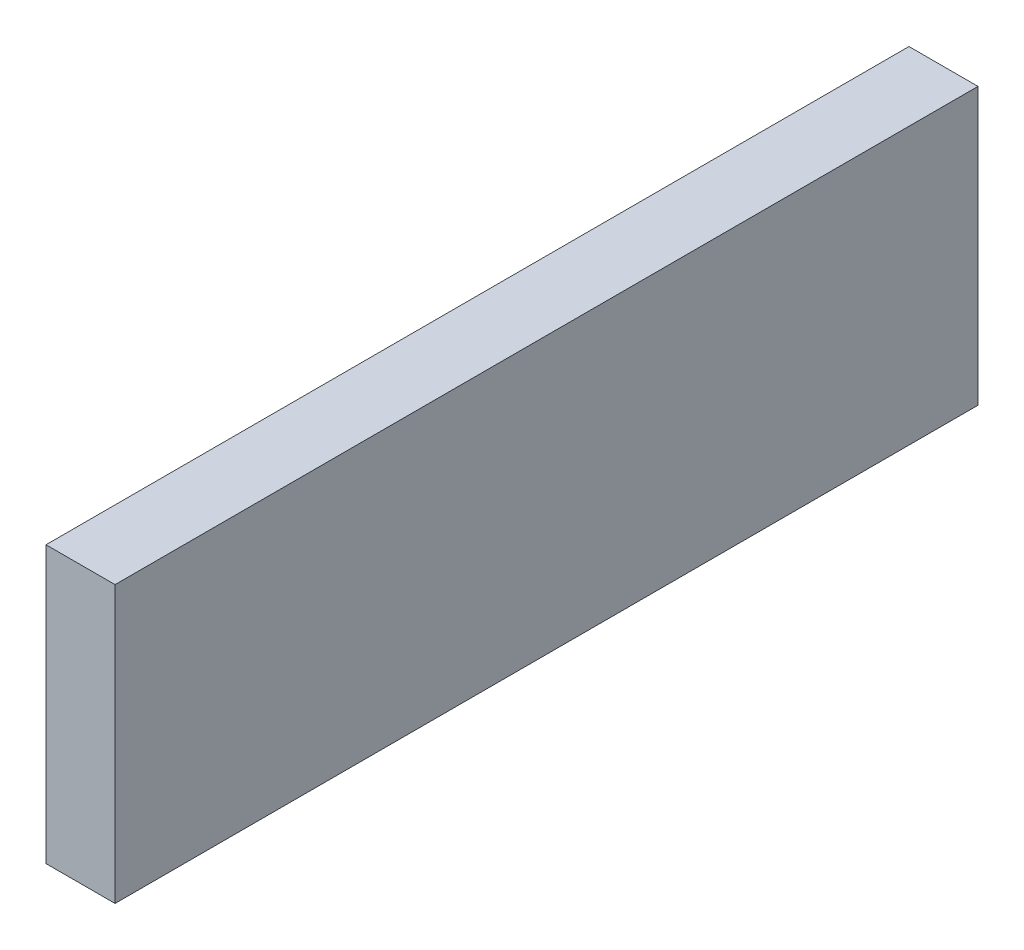
SolidWorks part; units mm, degrees
ref_plane "Front Plane" through (0, 0, 0) normal (0, 0, 1) x (1, 0, 0)
ref_plane "Top Plane" through (0, 0, 0) normal (0, 1, 0) x (1, 0, 0)
ref_plane "Right Plane" through (0, 0, 0) normal (1, 0, 0) x (0, 0, -1)
sketch "Sketch3" plane through (0, 0, 0) normal (0, 0, 1) x (1, 0, 0)
  line L1 (10, -40) -> (-10, -40)
  line L2 (10, -40) -> (10, 40)
  line L3 (10, 40) -> (-10, 40)
  line L4 (-10, -40) -> (-10, 40)
  line L5 (10, -40) -> (-10, 40) construction
  line L6 (10, 40) -> (-10, -40) construction
  point P0 (0, 0)
  dimension "D1" = 20
  dimension "D2" = 80
extrude "Boss-Extrude1" add sketch "Sketch3" along normal blind 250
